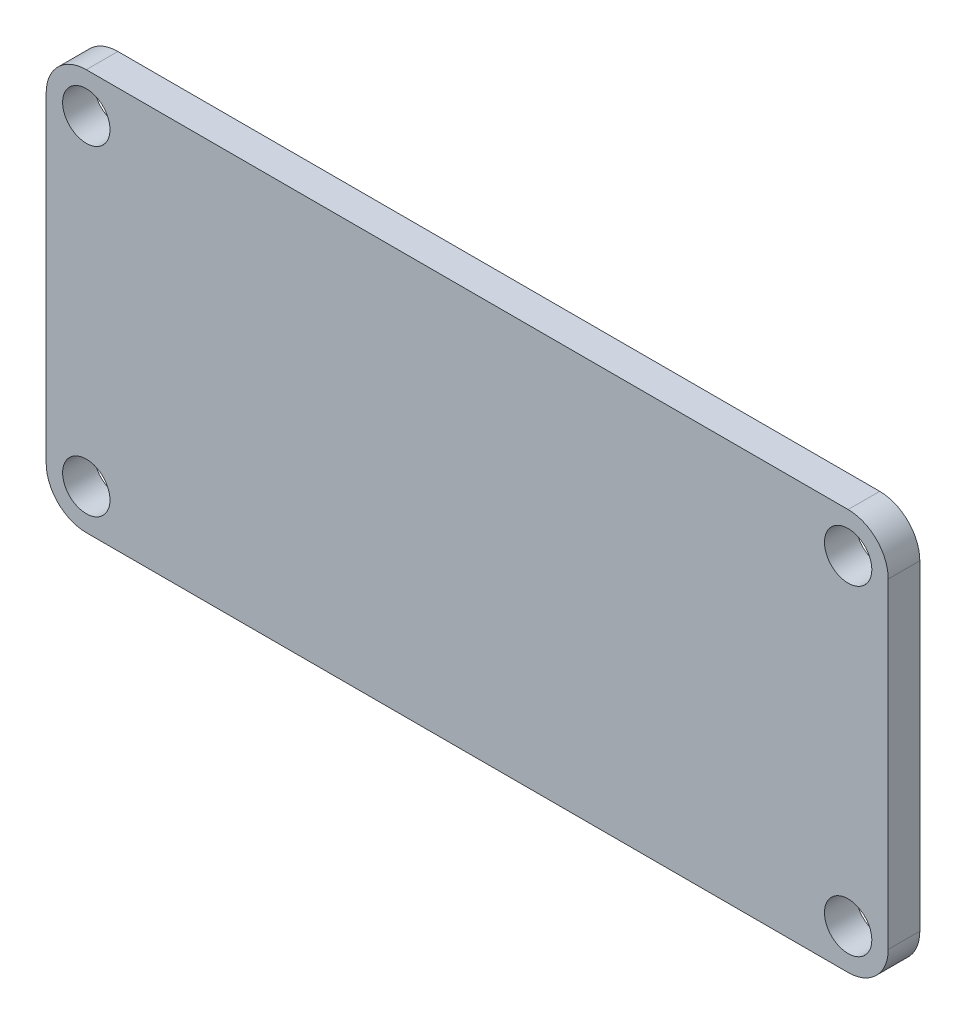
SolidWorks part; units mm, degrees
ref_plane "Alzado" through (0, 0, 0) normal (0, 0, 1) x (1, 0, 0)
ref_plane "Planta" through (0, 0, 0) normal (0, 1, 0) x (1, 0, 0)
ref_plane "Vista lateral" through (0, 0, 0) normal (1, 0, 0) x (0, 0, -1)
sketch "Croquis1" plane through (0, 0, 0) normal (0, 0, 1) x (1, 0, 0)
  line L1 (2.54, 0) -> (50.8, 0)
  line L2 (0, 2.54) -> (0, 22.86)
  line L3 (2.54, 25.4) -> (50.8, 25.4)
  line L4 (53.34, 2.54) -> (53.34, 22.86)
  arc A0 (50.8, 25.4) -> (53.34, 22.86) centre (50.8, 22.86) cw
  arc A1 (53.34, 2.54) -> (50.8, 0) centre (50.8, 2.54) cw
  arc A2 (0, 2.54) -> (2.54, 0) centre (2.54, 2.54) ccw
  arc A3 (0, 22.86) -> (2.54, 25.4) centre (2.54, 22.86) cw
  circle A4 centre (2.54, 22.86) radius 1.5
  circle A5 centre (50.8, 22.86) radius 1.5
  circle A6 centre (50.8, 2.54) radius 1.5
  circle A7 centre (2.54, 2.54) radius 1.5
  point P7 (53.34, 25.4)
  point P12 (0, 0)
  point P15 (0, 25.4)
  dimension "D3" = 2.54
  dimension "D4" = 3
  dimension "D1" = 25.4
  dimension "D2" = 53.34
extrude "Saliente-Extruir1" add sketch "Croquis1" along normal blind 2
